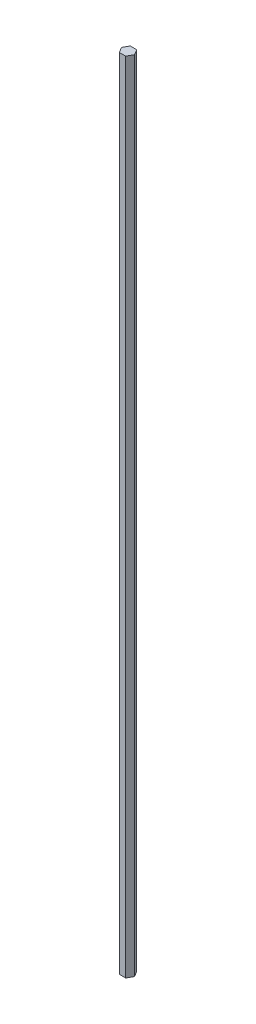
SolidWorks part; units mm, degrees
ref_plane "Front Plane" through (0, 0, 0) normal (0, 0, 1) x (1, 0, 0)
ref_plane "Top Plane" through (0, 0, 0) normal (0, 1, 0) x (1, 0, 0)
ref_plane "Right Plane" through (0, 0, 0) normal (1, 0, 0) x (0, 0, -1)
sketch "Sketch1" plane through (0, 0, 0) normal (0, 1, 0) x (1, 0, 0)
  line L1 (7.3323, 0) -> (3.6662, 6.35)
  line L2 (3.6662, 6.35) -> (-3.6662, 6.35)
  line L3 (-3.6662, 6.35) -> (-7.3323, 0)
  line L4 (-7.3323, 0) -> (-3.6662, -6.35)
  line L5 (-3.6662, -6.35) -> (3.6662, -6.35)
  line L6 (3.6662, -6.35) -> (7.3323, 0)
  circle A0 centre (0, 0) radius 6.35 construction
  dimension "D1" = 6.35
extrude "Boss-Extrude1" add sketch "Sketch1" along normal blind 914.4
